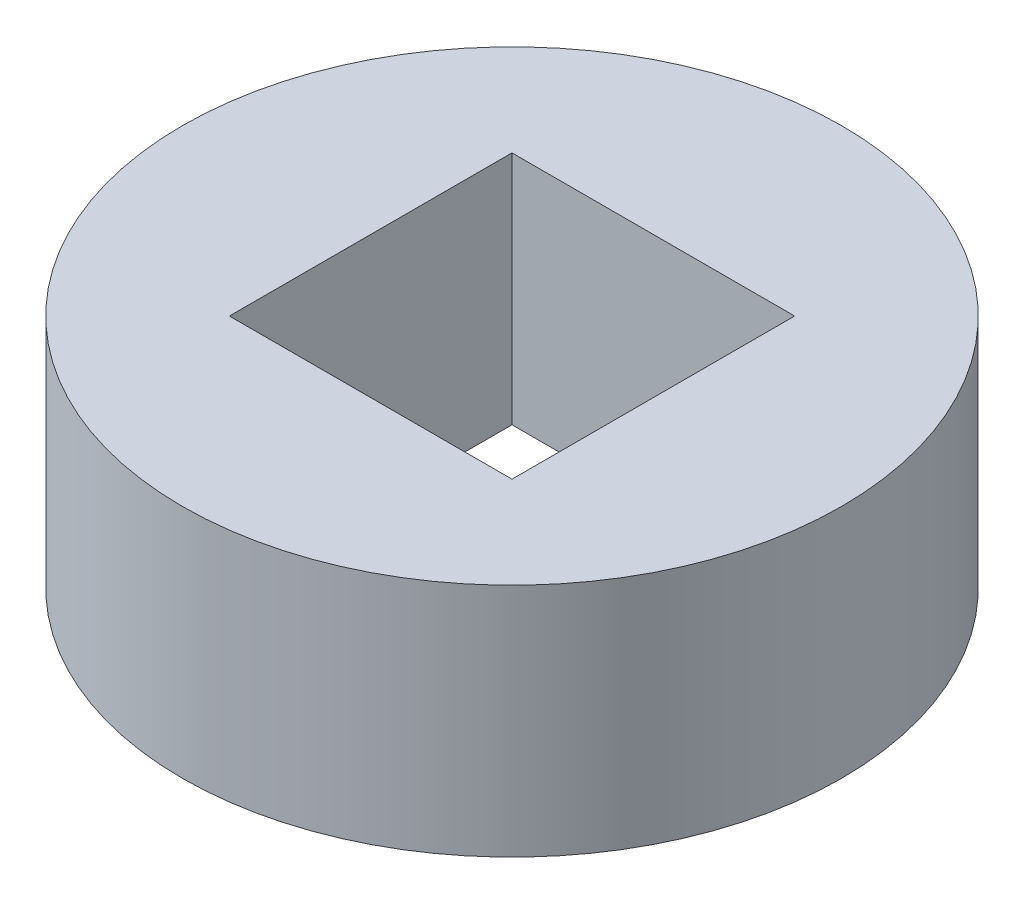
SolidWorks part; units mm, degrees
ref_plane "Front Plane" through (0, 0, 0) normal (0, 0, 1) x (1, 0, 0)
ref_plane "Top Plane" through (0, 0, 0) normal (0, 1, 0) x (1, 0, 0)
ref_plane "Right Plane" through (0, 0, 0) normal (1, 0, 0) x (0, 0, -1)
sketch "Sketch1" plane through (0, 0, 0) normal (0, 1, 0) x (1, 0, 0)
  line L1 (-3, -3) -> (3, -3)
  line L2 (-3, -3) -> (-3, 3)
  line L3 (-3, 3) -> (3, 3)
  line L4 (3, -3) -> (3, 3)
  line L5 (-3, -3) -> (3, 3) construction
  line L6 (-3, 3) -> (3, -3) construction
  circle A0 centre (0, 0) radius 7
  dimension "D1" = 14
  dimension "D2" = 6
  dimension "D3" = 6
extrude "Boss-Extrude1" add sketch "Sketch1" along normal blind 5
